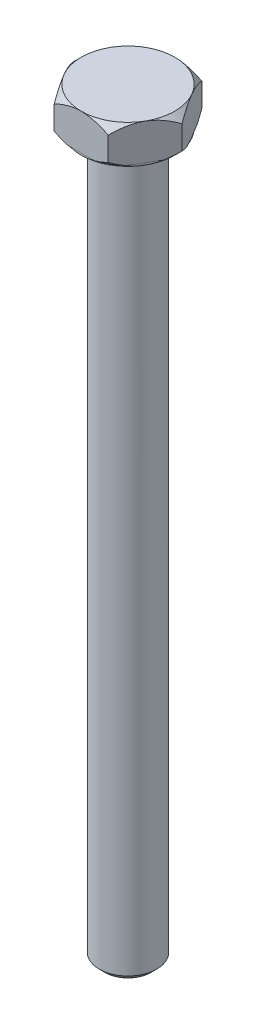
SolidWorks part; units mm, degrees
material "Cast Stainless Steel"
ref_plane "Front Plane" through (0, 0, 0) normal (0, 0, 1) x (1, 0, 0)
ref_plane "Top Plane" through (0, 0, 0) normal (0, 1, 0) x (1, 0, 0)
ref_plane "Right Plane" through (0, 0, 0) normal (1, 0, 0) x (0, 0, -1)
sketch "Sketch1" plane through (0, 0, 0) normal (0, 1, 0) x (1, 0, 0)
  line L0 (0, 0) -> (7.5056, 0) construction
  line L1 (7.5056, 0) -> (3.7528, 6.5)
  line L2 (3.7528, 6.5) -> (-3.7528, 6.5)
  line L3 (-3.7528, 6.5) -> (-7.5056, 0)
  line L4 (-7.5056, 0) -> (-3.7528, -6.5)
  line L5 (-3.7528, -6.5) -> (3.7528, -6.5)
  line L6 (3.7528, -6.5) -> (7.5056, 0)
  circle A0 centre (0, 0) radius 6.5 construction
  dimension "D1" = 13
extrude "Boss-Extrude1" add sketch "Sketch1" against normal blind 5.3
sketch "Sketch4" plane through (0, 0, 0) normal (1, 0, 0) x (0, 0, -1)
  line L0 (-6.5, 0) -> (-8.15, 0)
  line L1 (-8.15, 0) -> (-8.15, -1.65)
  line L2 (-8.15, -1.65) -> (-6.5, 0)
  line L3 (-6.5, -2.65) -> (6.5, -2.65) construction
  line L4 (-8.15, -3.65) -> (-6.5, -5.3)
  line L5 (-8.15, -5.3) -> (-8.15, -3.65)
  line L6 (-6.5, -5.3) -> (-8.15, -5.3)
  line L7 (0, 0) -> (0, -2.65) construction
  dimension "D1" = 45
  dimension "D2" = 2.65
  dimension "D3" = 1.65
  dimension "D4" = 13
revolve "Cut-Revolve1" cut sketch "Sketch4" angle 360 about L7
sketch "Sketch2" plane through (0, -5.3, 0) normal (0, -1, 0) x (1, 0, 0)
  circle A0 centre (0, 0) radius 6.5
  dimension "D1" = 13
extrude "Cut-Extrude1" cut sketch "Sketch2" against normal blind 0.265 flip side to cut
sketch "Sketch3" plane through (0, -5.3, 0) normal (0, -1, 0) x (1, 0, 0)
  circle A0 centre (0, 0) radius 4
  dimension "D1" = 8
extrude "Boss-Extrude2" add sketch "Sketch3" along normal blind 100
chamfer "Chamfer1" distance 0.8 angle 45 1 edges at (0, -105.3, -4)
equation "\"k\"= 5.3"
equation "\"e\"= 14.38"
equation "\"S\"= 13"
equation "\"L\"=100"
equation "\"D1@Sketch1\"=\"S\""
equation "\"D1@Boss-Extrude1\"=\"k\""
equation "\"D1@Sketch2\"=\"S\""
equation "\"D1@Cut-Extrude1\"=\"k\"/20"
equation "\"d\"= 8"
equation "\"D1@Sketch3\"=\"d\""
equation "\"D1@Boss-Extrude2\"=\"L\""
equation "\"D2@Sketch4\"=\"k\"/2"
equation "\"D3@Sketch4\"=\"D2@Sketch4\"-1"
equation "\"D4@Sketch4\"=\"S\""
equation "\"D1@Chamfer1\"=\"d\"/10"
